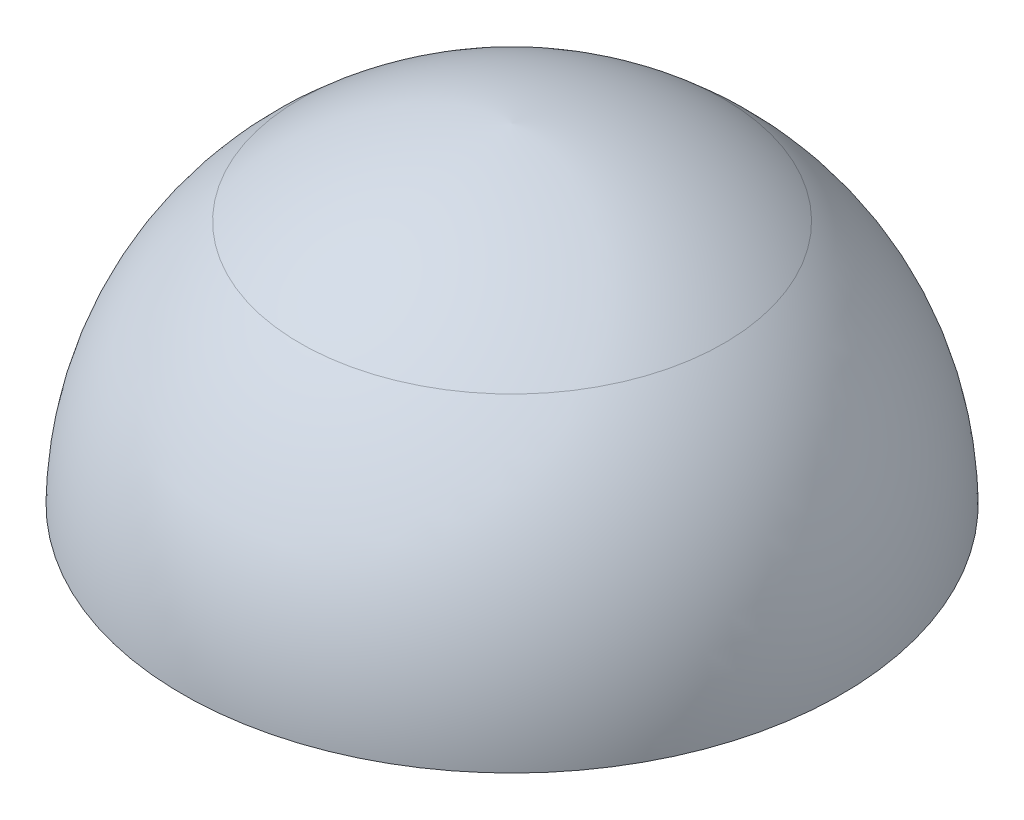
SolidWorks part; units mm, degrees
ref_plane "Front Plane" through (0, 0, 0) normal (0, 0, 1) x (1, 0, 0)
ref_plane "Top Plane" through (0, 0, 0) normal (0, 1, 0) x (1, 0, 0)
ref_plane "Right Plane" through (0, 0, 0) normal (1, 0, 0) x (0, 0, -1)
sketch "Sketch4" plane through (0, 0, 0) normal (1, 0, 0) x (0, 0, -1)
  line L0 (0, 0) -> (-4, 0)
  line L1 (0, 0) -> (0, 4)
  arc A0 (-4, 0) -> (-2.5704, 2.973) centre (-0.0625, -0.0632) cw
  arc A1 (-2.5704, 2.973) -> (0, 4) centre (0.3164, -0.5219) cw
  point P7 (-2.6082, 0)
  point P8 (-2.5704, 2.973)
  dimension "D2" = 4
  dimension "D1" = 4
revolve "Revolve1" add sketch "Sketch4" angle 360 about L1
shell "Shell1" thickness 2
